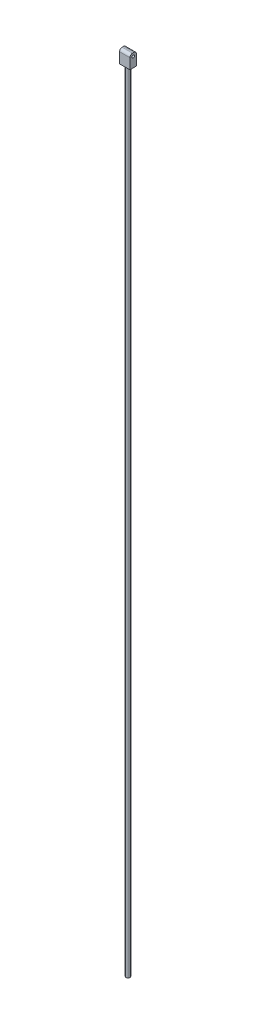
SolidWorks part; units mm, degrees
ref_plane "Front Plane" through (0, 0, 0) normal (0, 0, 1) x (1, 0, 0)
ref_plane "Top Plane" through (0, 0, 0) normal (0, 1, 0) x (1, 0, 0)
ref_plane "Right Plane" through (0, 0, 0) normal (1, 0, 0) x (0, 0, -1)
sketch "Sketch1" plane through (0, 0, 0) normal (0, 0, 1) x (1, 0, 0)
  line L1 (-3.95, 5) -> (3.95, 5)
  line L2 (-3.95, 5) -> (-3.95, -5)
  line L3 (-3.95, -5) -> (3.95, -5)
  line L4 (3.95, 5) -> (3.95, -5)
  line L5 (-3.95, 5) -> (3.95, -5) construction
  line L6 (-3.95, -5) -> (3.95, 5) construction
  point P0 (0, 0)
  dimension "D1" = 7.9
  dimension "D2" = 10
extrude "Boss-Extrude1" add sketch "Sketch1" along normal mid plane 5
fillet "Fillet2" radius 2 1 edges at (0, 5, -2.5)
fillet "Fillet3" radius 2 1 edges at (0, 5, 2.5)
sketch "Sketch4" plane through (3.95, 0, 0) normal (1, 0, 0) x (0, 0, -1)
  line L0 (-0.5, 5) -> (0.5, 5) construction
  circle A0 centre (0, 2.5) radius 1
  dimension "D2" = 2
  dimension "D1" = 2.5
extrude "Cut-Extrude1" cut sketch "Sketch4" against normal blind 10
sketch "Sketch5" plane through (0, -5, 0) normal (0, -1, 0) x (1, 0, 0)
  circle A0 centre (0, 0) radius 1.5
  dimension "D1" = 3
extrude "Boss-Extrude2" add sketch "Sketch5" along normal blind 600
